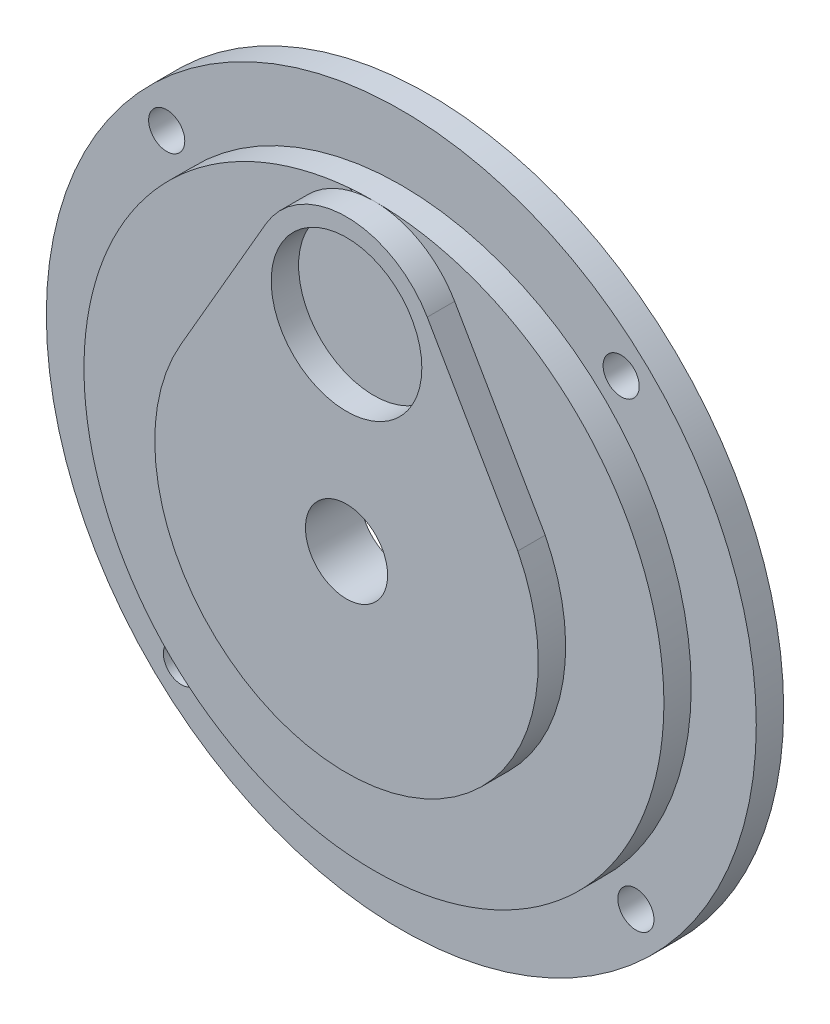
SolidWorks part; units mm, degrees
material "AISI 4130 Steel, annealed at 865C"
ref_plane "Front Plane" through (0, 0, 0) normal (0, 0, 1) x (1, 0, 0)
ref_plane "Top Plane" through (0, 0, 0) normal (0, 1, 0) x (1, 0, 0)
ref_plane "Right Plane" through (0, 0, 0) normal (1, 0, 0) x (0, 0, -1)
sketch "Sketch1" plane through (0, 0, 0) normal (0, 0, 1) x (1, 0, 0)
  circle A0 centre (-43.6736, 22.9437) radius 82.296
  circle A1 centre (-43.6736, 22.9437) radius 57.15
  circle A2 centre (-98.0611, 73.9107) radius 4.191
  circle A3 centre (7.2934, 77.3313) radius 4.191
  circle A4 centre (10.714, -28.0232) radius 4.191
  circle A5 centre (-94.6405, -31.4438) radius 4.191
extrude "Boss-Extrude1" add sketch "Sketch1" along normal blind 6.35
sketch "Sketch2" plane through (0, 0, 6.35) normal (0, 0, 1) x (1, 0, 0)
  circle A0 centre (-43.6736, 22.9437) radius 67.2114
  circle A1 centre (-43.6736, 22.9437) radius 9.525
  dimension "D1" = 19.05
extrude "Boss-Extrude2" add sketch "Sketch2" along normal blind 6.35
sketch "Sketch3" plane through (0, 0, 12.7) normal (0, 0, 1) x (1, 0, 0)
  line L0 (-43.6736, 22.9437) -> (-43.6736, 68.5367) construction
  line L1 (-62.386, 79.3626) -> (-82.1486, 45.2029)
  line L2 (-24.9611, 79.3626) -> (-3.9628, 42.9151)
  circle A0 centre (-43.6736, 68.5367) radius 17.4625
  circle A1 centre (-43.6736, 68.5367) radius 21.6184
  circle A2 centre (-43.6736, 22.9437) radius 44.45
  dimension "D1" = 34.925
  dimension "D2" = 88.9
  dimension "D3" = 45.593
extrude "Boss-Extrude3" add sketch "Sketch3" along normal blind 6.35
sketch "Sketch4" plane through (0, 0, 12.7) normal (0, 0, 1) x (1, 0, 0)
  circle A0 centre (-79.4188, 43.5812) radius 2.1526
  circle A1 centre (-7.9284, 43.5812) radius 2.1692
  circle A2 centre (-43.6736, -18.3313) radius 2.1526
extrude "Cut-Extrude1" cut sketch "Sketch4" against normal blind 13.97
